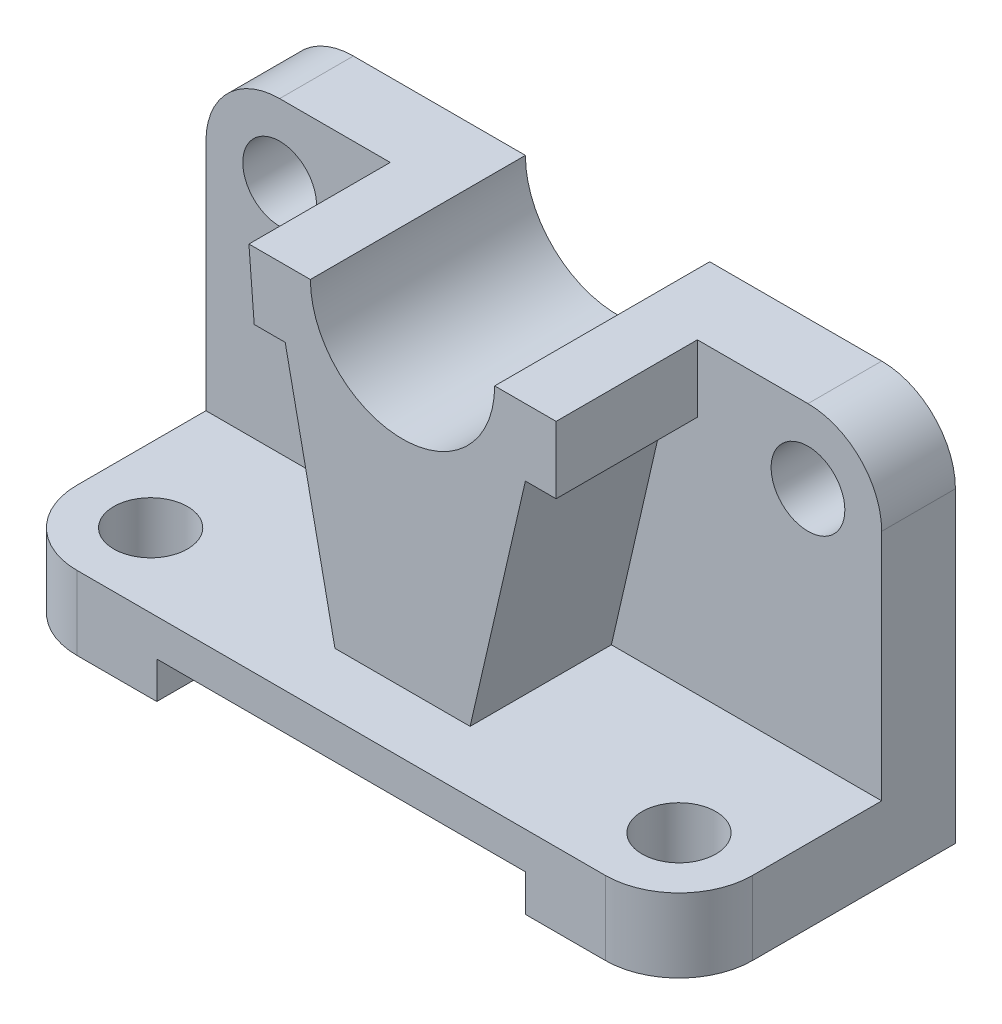
SolidWorks part; units mm, degrees
ref_plane "Front Plane" through (0, 0, 0) normal (0, 0, 1) x (1, 0, 0)
ref_plane "Top Plane" through (0, 0, 0) normal (0, 1, 0) x (1, 0, 0)
ref_plane "Right Plane" through (0, 0, 0) normal (1, 0, 0) x (0, 0, -1)
sketch "Sketch1" plane through (0, 0, 0) normal (1, 0, 0) x (0, 0, -1)
  line L0 (0, 0) -> (0, -62)
  line L1 (0, -62) -> (-45, -62)
  line L2 (-45, -62) -> (-45, -50)
  line L3 (-45, -50) -> (-12, -50)
  line L4 (-12, -50) -> (-12, 0)
  line L5 (-12, 0) -> (0, 0)
  dimension "D1" = 62
  dimension "D2" = 45
  dimension "D3" = 12
  dimension "D4" = 12
extrude "Boss-Extrude1" add sketch "Sketch1" along normal blind 110
sketch "Sketch4" plane through (0, 0, 12) normal (0, 0, 1) x (1, 0, 0)
  line L0 (30, 0) -> (40, 0)
  line L1 (110, 0) -> (0, 0) construction
  line L2 (70, 0) -> (80, 0)
  line L3 (80, 0) -> (80, -10.9134)
  line L4 (80, -10.9134) -> (75, -10.9134)
  line L5 (75, -10.9134) -> (66, -50)
  line L6 (110, -50) -> (0, -50) construction
  line L7 (66, -50) -> (44, -50)
  line L8 (44, -50) -> (35.9028, -10.9134)
  line L9 (35.9028, -10.9134) -> (30.8555, -10.9134)
  line L10 (30.8555, -10.9134) -> (30, 0)
  line L11 (110, 0) -> (110, -50) construction
  arc A0 (40, 0) -> (70, 0) centre (55, 0) ccw
  point P17 (55, -50)
  point P18 (55, -15)
  dimension "D1" = 55
  dimension "D2" = 50
  dimension "D3" = 30
  dimension "D4" = 35
  dimension "D5" = 55
  dimension "D6" = 22
  dimension "D7" = 15
extrude "Boss-Extrude2" add sketch "Sketch4" along normal blind 23
sketch "Sketch5" plane through (0, 0, 12) normal (0, 0, 1) x (1, 0, 0)
  line L1 (70, 0) -> (40, 0)
  line L2 (70, 0) -> (40, 0)
  arc A1 (40, 0) -> (70, 0) centre (55, 0) ccw
  arc A2 (40, 0) -> (70, 0) centre (55, 0) ccw
  dimension "D1" = 0
extrude "Cut-Extrude1" cut sketch "Sketch5" against normal blind 23
sketch "Sketch6" plane through (0, 0, 45) normal (0, 0, 1) x (1, 0, 0)
  line L0 (110, -62) -> (0, -62) construction
  line L1 (25, -62) -> (85, -62)
  line L2 (25, -62) -> (25, -56)
  line L3 (25, -56) -> (85, -56)
  line L4 (85, -62) -> (85, -56)
  line L5 (110, -50) -> (110, -62) construction
  dimension "D1" = 60
  dimension "D2" = 6
  dimension "D3" = 25
extrude "Cut-Extrude2" cut sketch "Sketch6" against normal blind 153
fillet "Fillet1" radius 12 2 edges at (110, -56, 45) (0, -56, 45)
sketch "Sketch9" plane through (0, -50, 0) normal (0, 1, 0) x (1, 0, 0)
  circle A0 centre (12, -33) radius 6
  dimension "D1" = 12
extrude "Cut-Extrude3" cut sketch "Sketch9" against normal blind 153
ref_plane "Plane1" through (55, 0, 0) normal (-1, 0, 0) x (0, 0, 1)
mirror "Mirror1" about plane through (55, 0, 0) normal (-1, 0, 0) of "Cut-Extrude3"
fillet "Fillet3" radius 12 2 edges at (110, 0, 6) (0, 0, 6)
sketch "Sketch10" plane through (0, 0, 0) normal (0, 0, -1) x (-1, 0, 0)
  circle A0 centre (-12, -12) radius 6
  dimension "D1" = 12
extrude "Cut-Extrude4" cut sketch "Sketch10" against normal blind 153
sketch "Sketch11" plane through (0, 0, 12) normal (0, 0, 1) x (1, 0, 0)
  circle A0 centre (98, -12) radius 6
extrude "Cut-Extrude5" cut sketch "Sketch11" against normal blind 153
